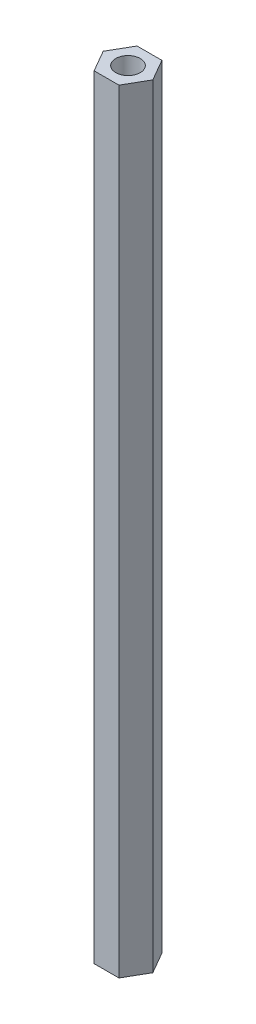
SolidWorks part; units mm, degrees
ref_plane "Front Plane" through (0, 0, 0) normal (0, 0, 1) x (1, 0, 0)
ref_plane "Top Plane" through (0, 0, 0) normal (0, 1, 0) x (1, 0, 0)
ref_plane "Right Plane" through (0, 0, 0) normal (1, 0, 0) x (0, 0, -1)
sketch "Sketch1" plane through (0, 0, 0) normal (0, 1, 0) x (1, 0, 0)
  line L1 (4.0415, 0) -> (2.0207, 3.5)
  line L2 (2.0207, 3.5) -> (-2.0207, 3.5)
  line L3 (-2.0207, 3.5) -> (-4.0415, 0)
  line L4 (-4.0415, 0) -> (-2.0207, -3.5)
  line L5 (-2.0207, -3.5) -> (2.0207, -3.5)
  line L6 (2.0207, -3.5) -> (4.0415, 0)
  circle A0 centre (0, 0) radius 3.5 construction
  circle A1 centre (0, 0) radius 2
  dimension "D1" = 4
  dimension "D2" = 7
extrude "Boss-Extrude1" add sketch "Sketch1" along normal blind 126
